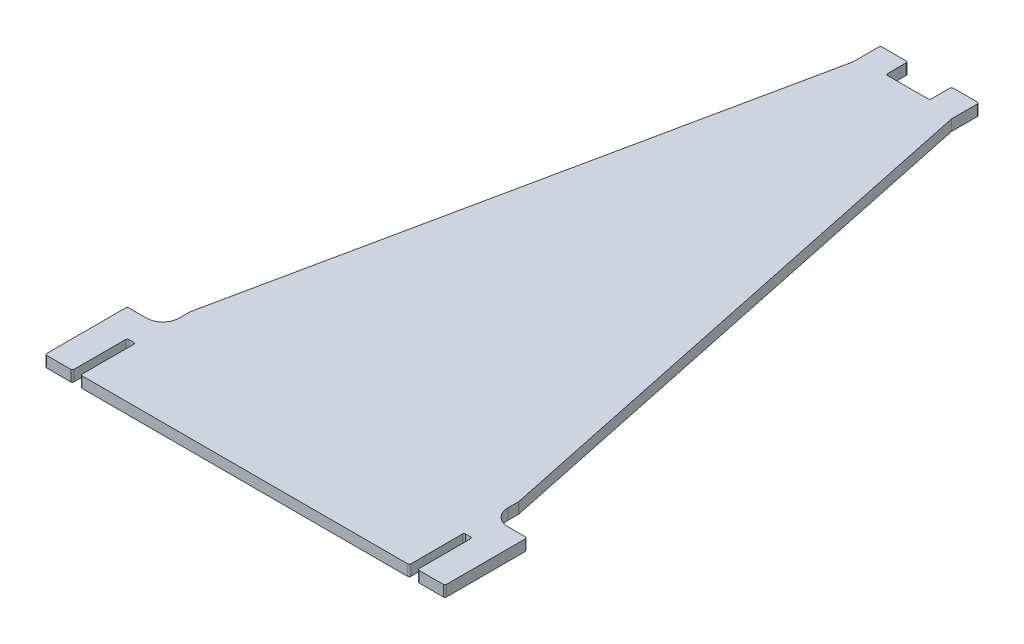
SolidWorks part; units mm, degrees
ref_plane "Front Plane" through (0, 0, 0) normal (0, 0, 1) x (1, 0, 0)
ref_plane "Top Plane" through (0, 0, 0) normal (0, 1, 0) x (1, 0, 0)
ref_plane "Right Plane" through (0, 0, 0) normal (1, 0, 0) x (0, 0, -1)
sketch "Sketch1" plane through (0, 0, 0) normal (0, 1, 0) x (1, 0, 0)
  line L0 (0, 0) -> (0, 1.5)
  line L1 (0, 1.5) -> (0.65, 1.5)
  line L2 (0.65, 1.5) -> (0.65, 2)
  line L3 (0.65, 2) -> (2.75, 12)
  line L4 (2.75, 12) -> (2.75, 12.5)
  line L5 (2.75, 12.5) -> (3.25, 12.5)
  line L6 (3.25, 12.5) -> (3.25, 12.1)
  line L7 (3.25, 12.1) -> (4.05, 12.1)
  line L8 (4.05, 12.1) -> (4.05, 12.5)
  line L9 (4.05, 12.5) -> (4.55, 12.5)
  line L10 (4.55, 12.5) -> (4.55, 12)
  line L11 (4.55, 12) -> (6.65, 2)
  line L12 (6.65, 2) -> (6.65, 1.5)
  line L13 (6.65, 1.5) -> (7.3, 1.5)
  line L14 (7.3, 1.5) -> (7.3, 0)
  line L15 (7.3, 0) -> (6.8, 0)
  line L16 (6.8, 0) -> (6.8, 1)
  line L17 (6.8, 1) -> (6.65, 1)
  line L18 (6.65, 1) -> (6.65, 0)
  line L19 (6.65, 0) -> (0.65, 0)
  line L20 (0.65, 0) -> (0.65, 1)
  line L21 (0.65, 1) -> (0.5, 1)
  line L22 (0.5, 1) -> (0.5, 0)
  line L23 (0.5, 0) -> (0, 0)
  point P3 (3.65, 12.1)
  point P27 (3.65, 0)
  dimension "D1" = 6
  dimension "D2" = 10
  dimension "D3" = 0.15
  dimension "D4" = 0.5
  dimension "D5" = 1
  dimension "D6" = 0.5
  dimension "D7" = 0.5
  dimension "D8" = 0.4
  dimension "D9" = 0.5
  dimension "D10" = 0.5
  dimension "D11" = 1.8
extrude "Boss-Extrude1" add sketch "Sketch1" along normal blind 0.2
fillet "Fillet1" radius 0.3 2 edges at (0.65, 0.1, -1.5) (6.65, 0.1, -1.5)
fillet "Fillet2" radius 0.03 22 edges at (6.8, 0.1, -1) (6.65, 0.1, -1) (7.3, 0.1, 0) (6.8, 0.1, 0) (6.65, 0.1, 0) (7.3, 0.1, -1.5) (6.65, 0.1, -2) (4.55, 0.1, -12) (4.55, 0.1, -12.5) (4.05, 0.1, -12.5) (4.05, 0.1, -12.1) (3.25, 0.1, -12.1) (3.25, 0.1, -12.5) (2.75, 0.1, -12.5) (2.75, 0.1, -12) (0.65, 0.1, -2) (0.65, 0.1, 0) (0.65, 0.1, -1) (0.5, 0.1, -1) (0.5, 0.1, 0) (0, 0.1, -1.5) (0, 0.1, 0)
